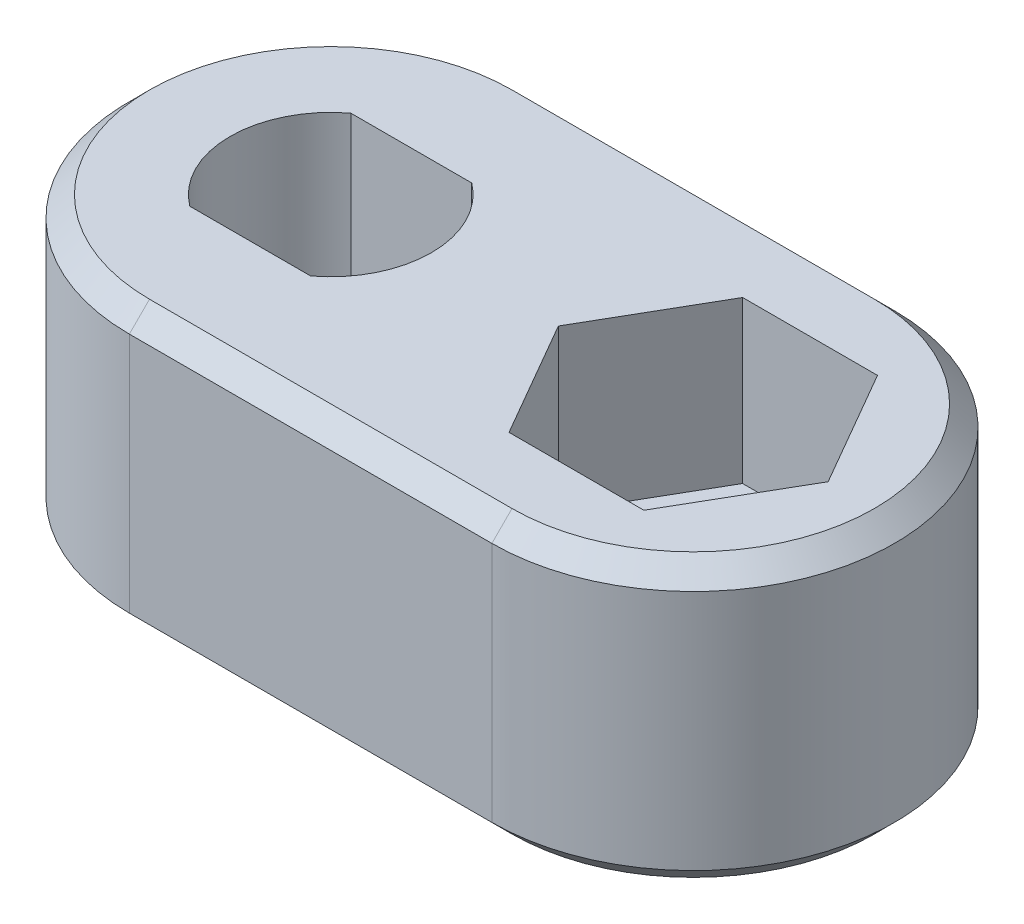
SolidWorks part; units mm, degrees
ref_plane "前视基准面" through (0, 0, 0) normal (0, 0, 1) x (1, 0, 0)
ref_plane "上视基准面" through (0, 0, 0) normal (0, 1, 0) x (1, 0, 0)
ref_plane "右视基准面" through (0, 0, 0) normal (1, 0, 0) x (0, 0, -1)
sketch "草图1" plane through (0, 0, 0) normal (0, 1, 0) x (1, 0, 0)
  line L0 (0, 0) -> (9, 0) construction
  line L1 (0, 5) -> (9, 5)
  line L2 (0, -5) -> (9, -5)
  arc A0 (0, 5) -> (0, -5) centre (0, 0) ccw
  arc A1 (9, -5) -> (9, 5) centre (9, 0) ccw
  point P3 (4.5, 0)
  dimension "D1" = 10
  dimension "D2" = 9
extrude "凸台-拉伸1" add sketch "草图1" along normal blind 7
sketch "草图2" plane through (0, 7, 0) normal (0, 1, 0) x (1, 0, 0)
  line L0 (-1.5, -2) -> (1.5, -2)
  line L1 (-1.5, 2) -> (1.5, 2)
  line L2 (0, 0) -> (3.4959, 0) construction
  circle A0 centre (0, 0) radius 2.5
  dimension "D1" = 5
  dimension "D2" = 4
extrude "切除-拉伸1" cut sketch "草图2" against normal blind 4
hole_wizard "M3 六角凹锥坑螺钉的锥形沉头孔1" positions "草图3" profile "草图4" countersink size "M3" standard "ISO"
sketch "草图3" plane through (0, 0, 0) normal (0, -1, 0) x (-1, 0, 0)
  point P0 (0, 0)
sketch "草图4" plane through (0, 0, 0) normal (1, 0, 0) x (0, 0, -1)
  line L0 (0, 0) -> (0, 8.5215)
  line L1 (0, 8.5215) -> (1.7, 7.5)
  line L2 (1.7, 7.5) -> (1.7, 1.66)
  line L3 (1.7, 1.66) -> (3.36, 0)
  line L5 (3.36, 0) -> (0, 0)
  line L6 (-1.7, 1.66) -> (-3.36, 0) construction
  line L10 (0, 8.5215) -> (-1.7, 7.5) construction
  line L11 (0, -6.35) -> (0, 107.95) construction
  dimension "孔直径" = 3.4
  dimension "孔深度" = 7.5
  dimension "近端锥形沉头孔直径" = 6.72
  dimension "近端锥形沉头孔角度" = 90
  dimension "导头角度" = 118
hole_wizard "孔1" positions "草图5" profile "草图6" legacy end condition through all
sketch "草图5" plane through (0, 0, 0) normal (0, -1, 0) x (-1, 0, 0)
  point P0 (-9, 0)
sketch "草图6" plane through (9, 0, 0) normal (1, 0, 0) x (0, 0, -1)
  line L0 (0, 0) -> (0, 7)
  line L1 (0, 7) -> (2.075, 7)
  line L2 (2.075, 7) -> (2.075, 0)
  line L3 (2.075, 0) -> (0, 0)
  line L4 (0, 110) -> (0, -10) construction
  dimension "直径" = 4.15
  dimension "深度" = 7
sketch "草图7" plane through (0, 7, 0) normal (0, 1, 0) x (1, 0, 0)
  line L0 (9, 5) -> (0, 5) construction
  line L1 (12.3486, 0) -> (10.6743, 2.9)
  line L2 (10.6743, 2.9) -> (7.3257, 2.9)
  line L3 (7.3257, 2.9) -> (5.6514, 0)
  line L4 (5.6514, 0) -> (7.3257, -2.9)
  line L5 (7.3257, -2.9) -> (10.6743, -2.9)
  line L6 (10.6743, -2.9) -> (12.3486, 0)
  circle A0 centre (9, 0) radius 2.9 construction
  dimension "D1" = 5.8
extrude "切除-拉伸2" cut sketch "草图7" against normal blind 4
chamfer "倒角1" distance 0.5 angle 45 8 edges at (4.5, 7, -5) (-5, 7, 0) (14, 7, 0) (4.5, 7, 5) (4.5, 0, -5) (-5, 0, 0) (14, 0, 0) (4.5, 0, 5)
